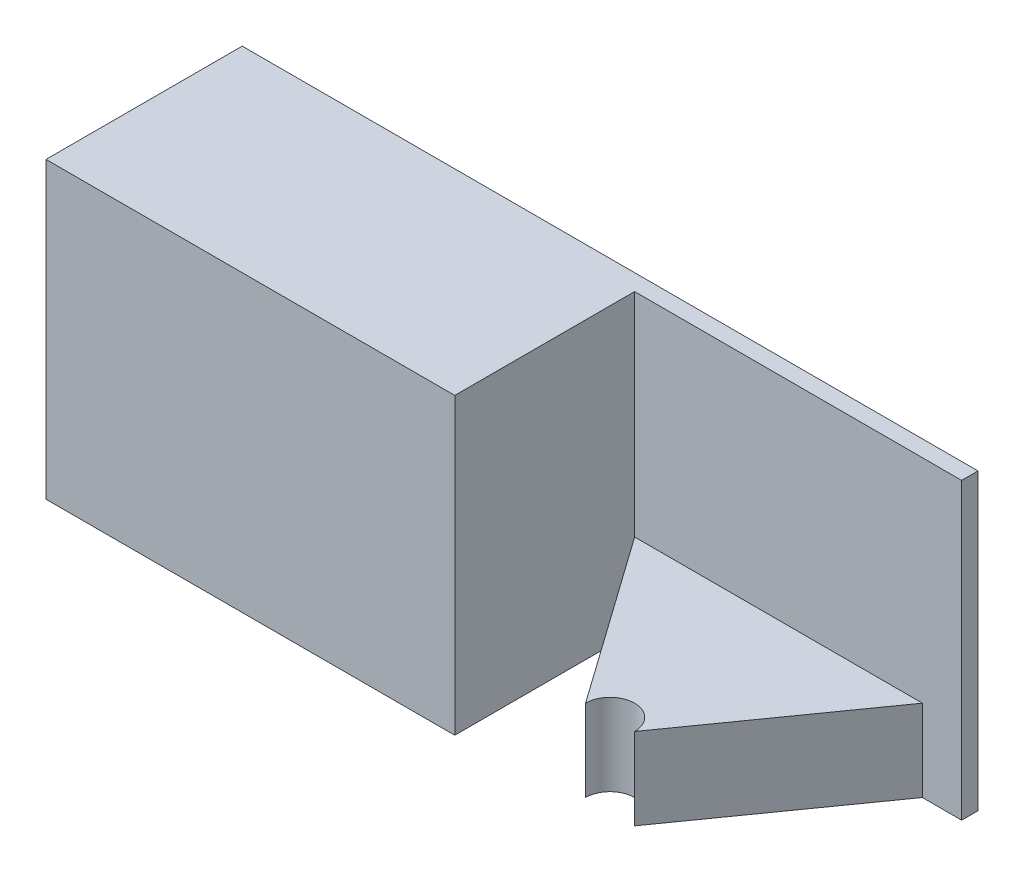
SolidWorks part; units mm, degrees
ref_plane "Front Plane" through (0, 0, 0) normal (0, 0, 1) x (1, 0, 0)
ref_plane "Top Plane" through (0, 0, 0) normal (0, 1, 0) x (1, 0, 0)
ref_plane "Right Plane" through (0, 0, 0) normal (1, 0, 0) x (0, 0, -1)
sketch "Sketch2" plane through (0, 0, 0) normal (0, 1, 0) x (1, 0, 0)
  line L1 (-125, -60) -> (125, -60)
  line L2 (-125, -60) -> (-125, 60)
  line L3 (-125, 60) -> (125, 60)
  line L4 (125, -60) -> (125, 60)
  line L5 (-125, -60) -> (125, 60) construction
  line L6 (-125, 60) -> (125, -60) construction
  point P0 (0, 0)
  dimension "D1" = 250
  dimension "D2" = 120
extrude "Boss-Extrude1" add sketch "Sketch2" along normal blind 180
sketch "Sketch3" plane through (0, 0, -60) normal (0, 0, -1) x (-1, 0, 0)
  line L0 (-325, 180) -> (-325, 0)
  line L4 (-125, 0) -> (125, 0)
  line L5 (125, 0) -> (125, 180)
  line L6 (125, 180) -> (-125, 180)
  line L7 (-125, 180) -> (-125, 0)
  line L8 (-325, 0) -> (125, 0)
  line L9 (125, 0) -> (125, 180)
  line L10 (125, 180) -> (-325, 180)
  dimension "D2" = 450
  dimension "D3" = 450
  dimension "D1" = 0
extrude "Boss-Extrude2" add sketch "Sketch3" against normal blind 10
sketch "Sketch4" plane through (0, 0, 0) normal (0, -1, 0) x (1, 0, 0)
  line L0 (125, -50) -> (300.98, -50)
  line L1 (325, -50) -> (125, -50) construction
  line L2 (197.99, 53) -> (125, -50)
  line L3 (227.99, 53) -> (300.98, -50)
  line L4 (125, 60) -> (125, -50) construction
  arc A0 (197.99, 53) -> (227.99, 53) centre (212.99, 53) ccw
  dimension "D2" = 30
  dimension "D1" = 103
  dimension "D3" = 87.99
extrude "Boss-Extrude3" add sketch "Sketch4" against normal blind 50
